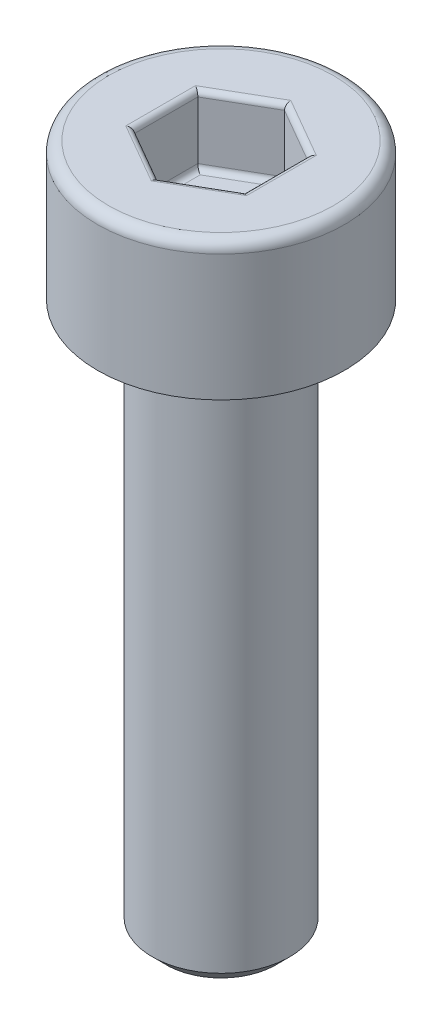
SolidWorks part; units mm, degrees
ref_plane "Front Plane" through (0, 0, 0) normal (0, 0, 1) x (1, 0, 0)
ref_plane "Top Plane" through (0, 0, 0) normal (0, 1, 0) x (1, 0, 0)
ref_plane "Right Plane" through (0, 0, 0) normal (1, 0, 0) x (0, 0, -1)
sketch "Sketch1" plane through (0, 0, 0) normal (0, 0, 1) x (1, 0, 0)
  line L0 (0, 0) -> (0, -47.0967) construction
  line L1 (0, -12.5) -> (-1.25, -12.5)
  line L2 (-1.25, -12.5) -> (-1.25, -2.5)
  line L3 (-1.25, -2.5) -> (-2.25, -2.5)
  line L4 (-2.25, -2.5) -> (-2.25, 0)
  line L5 (-2.25, 0) -> (0, 0)
  line L6 (0, 0) -> (0, -12.5)
  dimension "d" = 2.5
  dimension "l" = 12.5
  dimension "k" = 2.5
  dimension "dk" = 4.5
revolve "Revolve1" add sketch "Sketch1" angle 360 about L0
chamfer "Chamfer1" distance 0.25 angle 45 2 edges at (0, -2.5, 1.25) (0, -12.5, 1.25)
fillet "Fillet1" radius 0.2 1 edges at (0, 0, 2.25)
sketch "Sketch2" plane through (0, 0, 0) normal (0, 1, 0) x (1, 0, 0)
  line L1 (0, 1.1547) -> (-1, 0.5774)
  line L2 (-1, 0.5774) -> (-1, -0.5774)
  line L3 (-1, -0.5774) -> (0, -1.1547)
  line L4 (0, -1.1547) -> (1, -0.5774)
  line L5 (1, -0.5774) -> (1, 0.5774)
  line L6 (1, 0.5774) -> (0, 1.1547)
  circle A0 centre (0, 0) radius 1 construction
  dimension "s" = 2
extrude "Cut-Extrude1" cut sketch "Sketch2" against normal blind 1.25
fillet "Fillet2" radius 0.1 12 edges at (-0.5, 0, -0.866) (-1, 0, 0) (-0.5, 0, 0.866) (0.5, 0, 0.866) (1, 0, 0) (0.5, 0, -0.866) (1, -1.25, 0) (0.5, -1.25, 0.866) (-0.5, -1.25, 0.866) (-1, -1.25, 0) (-0.5, -1.25, -0.866) (0.5, -1.25, -0.866)
